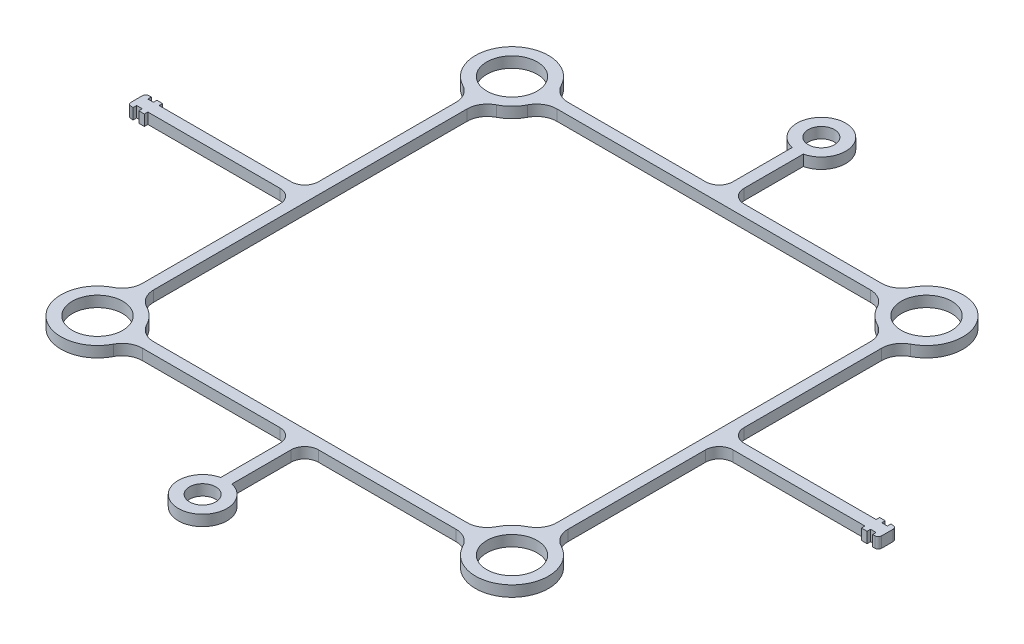
SolidWorks part; units mm, degrees
material "Custom Plastic"
ref_plane "Front Plane" through (0, 0, 0) normal (0, 0, 1) x (1, 0, 0)
ref_plane "Top Plane" through (0, 0, 0) normal (0, 1, 0) x (1, 0, 0)
ref_plane "Right Plane" through (0, 0, 0) normal (1, 0, 0) x (0, 0, -1)
sketch "Sketch1" plane through (0, 0, 0) normal (0, 1, 0) x (1, 0, 0)
  line L0 (0, 0.7578) -> (0, 24.4542) construction
  line L1 (-30.445, -29.6872) -> (30.445, -29.6872) construction
  line L2 (-30.445, -29.6872) -> (-30.445, 31.2028) construction
  line L3 (-30.445, 31.2028) -> (30.445, 31.2028) construction
  line L4 (30.445, -29.6872) -> (30.445, 31.2028) construction
  line L5 (-30.445, -29.6872) -> (30.445, 31.2028) construction
  line L6 (-30.445, 31.2028) -> (30.445, -29.6872) construction
  line L7 (-20.9637, 0.7578) -> (0, 0.7578) construction
  line L8 (-25.1489, 32.0278) -> (-0.825, 32.0278)
  line L9 (-25.1489, 30.3778) -> (25.1489, 30.3778)
  line L10 (0, 31.2028) -> (0, 46.2028) construction
  line L11 (-0.825, 42.7243) -> (-0.825, 32.0278)
  line L12 (0.825, 42.7243) -> (0.825, 32.0278)
  line L13 (0.825, 32.0278) -> (25.1489, 32.0278)
  line L14 (0, -29.6872) -> (0, -44.6872) construction
  line L15 (-25.1489, -28.8622) -> (25.1489, -28.8622)
  line L16 (54.3198, 2.0928) -> (55.1448, -0.5772) construction
  line L17 (29.62, -24.391) -> (29.62, 25.9067)
  line L18 (31.27, 25.9067) -> (31.27, 1.5828)
  line L19 (0.825, -30.5122) -> (25.1489, -30.5122)
  line L20 (-25.1489, -30.5122) -> (-0.825, -30.5122)
  line L21 (0.825, -41.2086) -> (0.825, -30.5122)
  line L22 (-0.825, -41.2086) -> (-0.825, -30.5122)
  line L23 (54.3198, -0.5772) -> (55.1448, 2.0928) construction
  line L24 (-34.155, 31.2028) -> (-34.155, 88.2809) construction
  line L25 (34.155, 31.2028) -> (34.155, 88.2809) construction
  line L26 (52.6698, 2.0928) -> (53.4948, -0.5772) construction
  line L27 (31.27, -0.0672) -> (31.27, -24.391)
  line L28 (-30.445, 0.7578) -> (-55.445, 0.7578) construction
  line L29 (-31.27, -0.0672) -> (-52.6698, -0.0672)
  line L30 (-31.27, -0.0672) -> (-31.27, -24.391)
  line L31 (-31.27, 1.5828) -> (-52.6698, 1.5828)
  line L32 (-31.27, 25.9067) -> (-31.27, 1.5828)
  line L33 (-29.62, -24.391) -> (-29.62, 25.9067)
  line L34 (-53.4948, 1.5828) -> (-54.3198, 1.5828)
  line L35 (-52.6698, -0.5772) -> (-53.4948, -0.5772)
  line L36 (-52.6698, -0.5772) -> (-52.6698, -0.0672)
  line L37 (-52.6698, 2.0928) -> (-53.4948, 2.0928)
  line L38 (-53.4948, -0.5772) -> (-53.4948, -0.0672)
  line L39 (-52.6698, -0.5772) -> (-53.4948, 2.0928) construction
  line L40 (-52.6698, 2.0928) -> (-53.4948, -0.5772) construction
  line L41 (-54.3198, -0.5772) -> (-55.1448, -0.5772)
  line L42 (-54.3198, -0.5772) -> (-54.3198, -0.0672)
  line L43 (-54.3198, 2.0928) -> (-55.1448, 2.0928)
  line L44 (-55.1448, -0.5772) -> (-55.1448, 2.0928)
  line L45 (-54.3198, -0.5772) -> (-55.1448, 2.0928) construction
  line L46 (-54.3198, 2.0928) -> (-55.1448, -0.5772) construction
  line L47 (-52.6698, 1.5828) -> (-52.6698, 2.0928)
  line L48 (-53.4948, -0.0672) -> (-54.3198, -0.0672)
  line L49 (-53.4948, 1.5828) -> (-53.4948, 2.0928)
  line L50 (-54.3198, 1.5828) -> (-54.3198, 2.0928)
  line L51 (52.6698, -0.5772) -> (53.4948, 2.0928) construction
  line L52 (30.445, 0.7578) -> (55.445, 0.7578) construction
  line L53 (54.3198, 1.5828) -> (54.3198, 2.0928)
  line L54 (53.4948, 1.5828) -> (53.4948, 2.0928)
  line L55 (53.4948, -0.0672) -> (54.3198, -0.0672)
  line L56 (52.6698, 1.5828) -> (52.6698, 2.0928)
  line L57 (55.1448, -0.5772) -> (55.1448, 2.0928)
  line L58 (54.3198, 2.0928) -> (55.1448, 2.0928)
  line L59 (54.3198, -0.5772) -> (54.3198, -0.0672)
  line L60 (54.3198, -0.5772) -> (55.1448, -0.5772)
  line L61 (53.4948, -0.5772) -> (53.4948, -0.0672)
  line L62 (52.6698, 2.0928) -> (53.4948, 2.0928)
  line L63 (52.6698, -0.5772) -> (52.6698, -0.0672)
  line L64 (52.6698, -0.5772) -> (53.4948, -0.5772)
  line L65 (53.4948, 1.5828) -> (54.3198, 1.5828)
  line L66 (31.27, 1.5828) -> (52.6698, 1.5828)
  line L67 (31.27, -0.0672) -> (52.6698, -0.0672)
  arc A0 (-29.62, 25.9067) -> (-25.1489, 30.3778) centre (-30.445, 31.2028) ccw
  circle A1 centre (-30.445, 31.2028) radius 3.71
  circle A2 centre (30.445, 31.2028) radius 3.71
  arc A3 (25.1489, 32.0278) -> (31.27, 25.9067) centre (30.445, 31.2028) cw
  arc A4 (29.62, -24.391) -> (25.1489, -28.8622) centre (30.445, -29.6872) ccw
  circle A5 centre (30.445, -29.6872) radius 3.71
  arc A6 (-25.1489, -30.5122) -> (-31.27, -24.391) centre (-30.445, -29.6872) cw
  circle A7 centre (-30.445, -29.6872) radius 3.71
  circle A8 centre (0, 46.2028) radius 1.925
  arc A9 (0.825, 42.7243) -> (-0.825, 42.7243) centre (0, 46.2028) ccw
  circle A12 centre (0, -44.6872) radius 1.925
  arc A13 (0.825, -41.2086) -> (-0.825, -41.2086) centre (0, -44.6872) cw
  arc A16 (-25.1489, 32.0278) -> (-31.27, 25.9067) centre (-30.445, 31.2028) ccw
  arc A18 (29.62, 25.9067) -> (25.1489, 30.3778) centre (30.445, 31.2028) cw
  arc A20 (25.1489, -30.5122) -> (31.27, -24.391) centre (30.445, -29.6872) ccw
  arc A22 (-29.62, -24.391) -> (-25.1489, -28.8622) centre (-30.445, -29.6872) cw
  point P0 (0, 0)
  point P52 (-53.0823, 0.7578)
  point P65 (-54.7323, 0.7578)
  point P85 (54.7323, 0.7578)
  point P86 (53.0823, 0.7578)
  dimension "D1" = 1.65
  dimension "D2" = 15
  dimension "D5" = 7.42
  dimension "D6" = 3.85
  dimension "D8" = 1.65
  dimension "D12" = 0.825
  dimension "D3" = 0.825
  dimension "D4" = 0.825
  dimension "D7" = 68.31
  dimension "D9" = 0.825
  dimension "D10" = 0.825
  dimension "D11" = 0.825
  dimension "D18" = 2.67
  dimension "D19" = 2.67
  dimension "D20" = 0.825
  dimension "D21" = 0.825
  dimension "D22" = 0.825
  dimension "D23" = 0.825
extrude "Boss-Extrude1" add sketch "Sketch1" along normal blind 1.5875
fillet "Fillet1" radius 3 16 edges at (-25.1489, 0.7937, 30.5122) (-25.1489, 0.7937, 28.8622) (-29.62, 0.7937, 24.391) (-31.27, 0.7937, 24.391) (31.27, 0.7937, 24.391) (29.62, 0.7937, 24.391) (25.1489, 0.7937, 28.8622) (25.1489, 0.7937, 30.5122) (25.1489, 0.7937, -32.0278) (25.1489, 0.7937, -30.3778) (29.62, 0.7937, -25.9067) (31.27, 0.7937, -25.9067) (-25.1489, 0.7937, -32.0278) (-31.27, 0.7937, -25.9067) (-29.62, 0.7937, -25.9067) (-25.1489, 0.7937, -30.3778)
fillet "Fillet2" radius 2 8 edges at (-31.27, 0.7937, -1.5828) (-0.825, 0.7937, -32.0278) (0.825, 0.7937, -32.0278) (-0.825, 0.7937, 30.5122) (0.825, 0.7937, 30.5122) (31.27, 0.7937, -1.5828) (31.27, 0.7937, 0.0672) (-31.27, 0.7937, 0.0672)
fillet "Fillet3" radius 0.5 4 edges at (-55.1448, 0.7937, -2.0928) (-55.1448, 0.7937, 0.5772) (55.1448, 0.7937, -2.0928) (55.1448, 0.7937, 0.5772)
